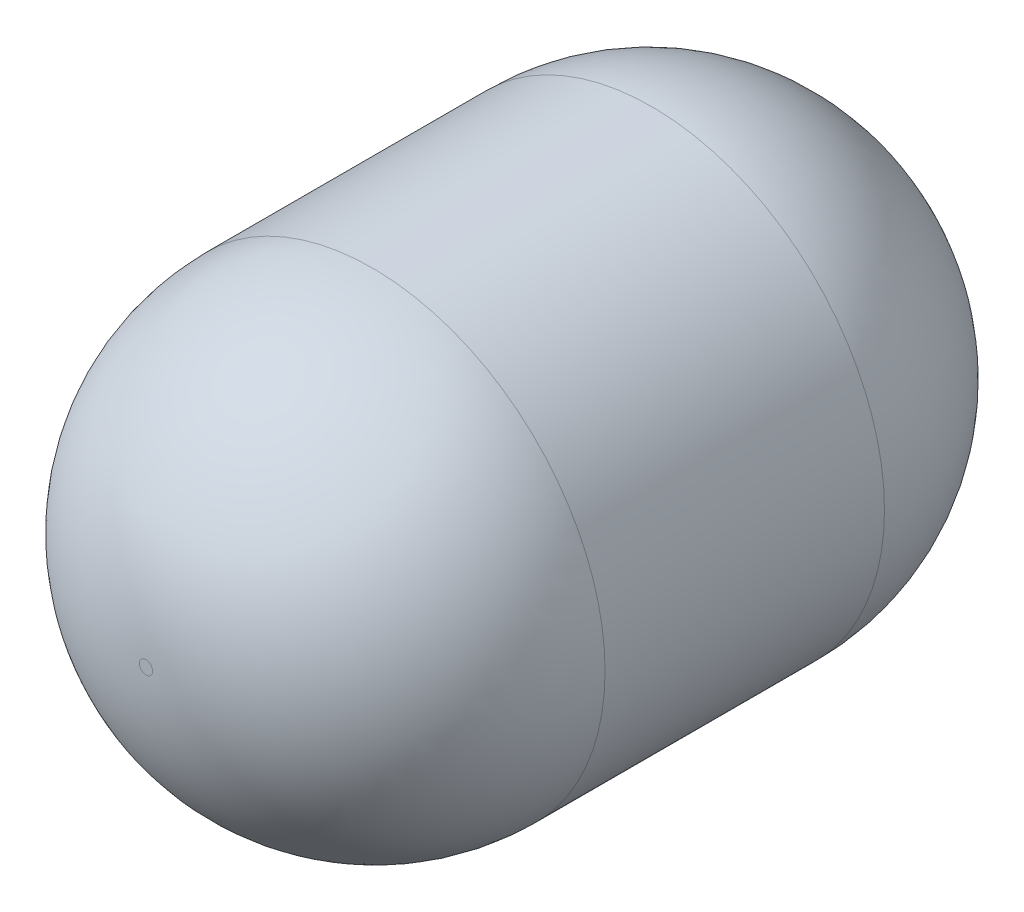
SolidWorks part; units mm, degrees
ref_plane "Front Plane" through (0, 0, 0) normal (0, 0, 1) x (1, 0, 0)
ref_plane "Top Plane" through (0, 0, 0) normal (0, 1, 0) x (1, 0, 0)
ref_plane "Right Plane" through (0, 0, 0) normal (1, 0, 0) x (0, 0, -1)
sketch "Sketch1" plane through (0, 0, 0) normal (0, 0, 1) x (1, 0, 0)
  circle A0 centre (0, 0) radius 35
  dimension "D1" = 70
extrude "Boss-Extrude1" add sketch "Sketch1" along normal blind 110
fillet "Fillet1" radius 34 2 edges at (35, 0, 0) (35, 0, 110)
